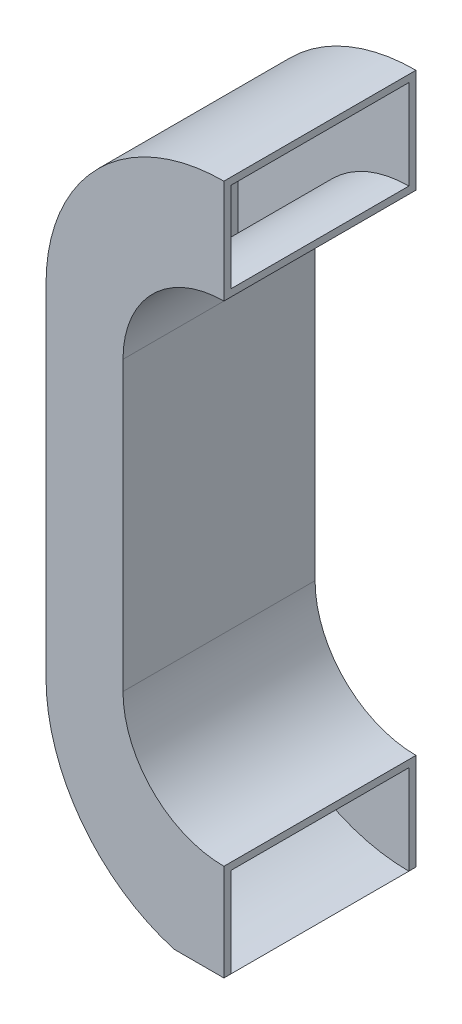
SolidWorks part; units mm, degrees
material "PE High Density"
ref_plane "Front Plane" through (0, 0, 0) normal (0, 0, 1) x (1, 0, 0)
ref_plane "Top Plane" through (0, 0, 0) normal (0, 1, 0) x (1, 0, 0)
ref_plane "Right Plane" through (0, 0, 0) normal (1, 0, 0) x (0, 0, -1)
sketch "Sketch2" plane through (0, 0, 0) normal (0, 0, 1) x (1, 0, 0)
  line L0 (0, 0) -> (0, 40)
  line L1 (0, 264.8) -> (0, 304.8)
  line L2 (-76.2, 76.2) -> (-76.2, 228.6)
  line L3 (0, 304.8) -> (-76.2, 304.8) construction
  line L4 (0, 304.8) -> (0, 0)
  line L5 (0, 0) -> (-76.2, 0) construction
  line L6 (-76.2, 304.8) -> (-76.2, 0) construction
  line L7 (-48.2, 88.2) -> (-48.2, 216.6)
  line L8 (-75.1148, 63.3856) -> (-26.4598, 4.7415) construction
  line L9 (-26.4598, 4.7415) -> (-6.9118, 20.9598) construction
  line L10 (-6.9118, 20.9598) -> (-55.5667, 79.6039) construction
  line L11 (-55.5667, 79.6039) -> (-75.1148, 63.3856) construction
  line L12 (0, 40) -> (25.7324, 40) construction
  line L13 (0, 264.8) -> (32.4991, 264.8) construction
  line L14 (0, 304.8) -> (0, 307.975)
  line L15 (0, 0) -> (-22.225, 0)
  line L16 (-45.025, 88.2) -> (-45.025, 216.6)
  line L17 (0, 261.625) -> (37.4536, 261.625) construction
  line L18 (0, 43.175) -> (15.6098, 43.175) construction
  line L19 (-79.375, 76.2) -> (-79.375, 228.6)
  line L20 (0, 307.975) -> (23.2649, 307.975) construction
  arc A0 (0, 304.8) -> (-76.2, 228.6) centre (0, 228.6) ccw
  arc A1 (0, 0) -> (-76.2, 76.2) centre (0, 76.2) cw
  arc A2 (0, 40) -> (-48.2, 88.2) centre (0, 88.2) cw
  arc A3 (0, 264.8) -> (-48.2, 216.6) centre (0, 216.6) ccw
  arc A4 (-45.025, 216.6) -> (0, 261.625) centre (0, 216.6) cw
  arc A5 (-45.025, 88.2) -> (0, 43.175) centre (0, 88.2) ccw
  arc A6 (-22.225, 0) -> (-79.375, 76.2) centre (0, 76.2) cw
  arc A7 (0, 307.975) -> (-79.375, 228.6) centre (0, 228.6) ccw
  dimension "D1" = 40
  dimension "D2" = 40
  dimension "D3" = 304.8
  dimension "D4" = 76.2
  dimension "D5" = 28
  dimension "D6" = 25.4
  dimension "D7" = 76.2
  dimension "D8" = 3.175
  dimension "D9" = 3.175
extrude "Boss-Extrude1" add sketch "Sketch2" along normal blind 79.375 contours L14 A7 L19 A6 L15 A1 L2 A0 | A5 L16 A4 L4 A3 L7 A2
sketch "Sketch3" plane through (0, 0, 79.375) normal (0, 0, 1) x (1, 0, 0)
  line L0 (-45.025, 88.2) -> (-45.025, 216.6) construction
  line L1 (0, 261.625) -> (0, 264.8) construction
  line L2 (-48.2, 216.6) -> (-48.2, 88.2) construction
  line L3 (0, 40) -> (0, 43.175) construction
  line L4 (0, 304.8) -> (0, 307.975) construction
  line L5 (-79.375, 228.6) -> (-79.375, 76.2) construction
  line L6 (-22.225, 0) -> (0, 0) construction
  line L7 (-76.2, 76.2) -> (-76.2, 228.6) construction
  line L8 (-45.025, 88.2) -> (-45.025, 216.6)
  line L9 (0, 261.625) -> (0, 264.8) construction
  line L10 (-48.2, 216.6) -> (-48.2, 88.2) construction
  line L11 (0, 40) -> (0, 43.175) construction
  line L12 (0, 304.8) -> (0, 307.975) construction
  line L13 (-79.375, 228.6) -> (-79.375, 76.2)
  line L14 (-22.225, 0) -> (0, 0) construction
  line L15 (-76.2, 76.2) -> (-76.2, 228.6) construction
  line L16 (0, 261.625) -> (0, 307.975)
  line L17 (0, 43.175) -> (0, 0)
  line L18 (0, 0) -> (-22.225, 0)
  arc A0 (-45.025, 88.2) -> (0, 43.175) centre (0, 88.2) ccw construction
  arc A1 (0, 261.625) -> (-45.025, 216.6) centre (0, 216.6) ccw construction
  arc A2 (0, 264.8) -> (-48.2, 216.6) centre (0, 216.6) ccw construction
  arc A3 (-48.2, 88.2) -> (0, 40) centre (0, 88.2) ccw construction
  arc A4 (0, 307.975) -> (-79.375, 228.6) centre (0, 228.6) ccw construction
  arc A5 (-79.375, 76.2) -> (-22.225, 0) centre (0, 76.2) ccw construction
  arc A6 (-76.2, 76.2) -> (0, 0) centre (0, 76.2) ccw construction
  arc A7 (0, 304.8) -> (-76.2, 228.6) centre (0, 228.6) ccw construction
  arc A8 (-45.025, 88.2) -> (0, 43.175) centre (0, 88.2) ccw
  arc A9 (0, 261.625) -> (-45.025, 216.6) centre (0, 216.6) ccw
  arc A10 (0, 264.8) -> (-48.2, 216.6) centre (0, 216.6) ccw construction
  arc A11 (-48.2, 88.2) -> (0, 40) centre (0, 88.2) ccw construction
  arc A12 (0, 307.975) -> (-79.375, 228.6) centre (0, 228.6) ccw
  arc A13 (-79.375, 76.2) -> (-22.225, 0) centre (0, 76.2) ccw
  arc A14 (-76.2, 76.2) -> (0, 0) centre (0, 76.2) ccw construction
  arc A15 (0, 304.8) -> (-76.2, 228.6) centre (0, 228.6) ccw construction
extrude "Boss-Extrude2" add sketch "Sketch3" along normal blind 3.175
sketch "Sketch4" plane through (0, 0, 0) normal (0, 0, -1) x (-1, 0, 0)
  line L0 (0, 307.975) -> (0, 304.8) construction
  line L1 (76.2, 228.6) -> (76.2, 76.2) construction
  line L2 (0, 0) -> (22.225, 0) construction
  line L3 (79.375, 76.2) -> (79.375, 228.6) construction
  line L4 (0, 43.175) -> (0, 40) construction
  line L5 (48.2, 88.2) -> (48.2, 216.6) construction
  line L6 (0, 264.8) -> (0, 261.625) construction
  line L7 (45.025, 216.6) -> (45.025, 88.2) construction
  line L8 (0, 307.975) -> (0, 304.8) construction
  line L9 (76.2, 228.6) -> (76.2, 76.2) construction
  line L10 (0, 0) -> (22.225, 0) construction
  line L11 (79.375, 76.2) -> (79.375, 228.6)
  line L12 (0, 43.175) -> (0, 40) construction
  line L13 (48.2, 88.2) -> (48.2, 216.6) construction
  line L14 (0, 264.8) -> (0, 261.625) construction
  line L15 (45.025, 216.6) -> (45.025, 88.2)
  line L16 (0, 307.975) -> (0, 261.625)
  line L17 (0, 43.175) -> (0, 0)
  line L18 (0, 0) -> (22.225, 0)
  arc A0 (76.2, 228.6) -> (0, 304.8) centre (0, 228.6) ccw construction
  arc A1 (0, 0) -> (76.2, 76.2) centre (0, 76.2) ccw construction
  arc A2 (22.225, 0) -> (79.375, 76.2) centre (0, 76.2) ccw construction
  arc A3 (79.375, 228.6) -> (0, 307.975) centre (0, 228.6) ccw construction
  arc A4 (0, 43.175) -> (45.025, 88.2) centre (0, 88.2) ccw construction
  arc A5 (0, 40) -> (48.2, 88.2) centre (0, 88.2) ccw construction
  arc A6 (48.2, 216.6) -> (0, 264.8) centre (0, 216.6) ccw construction
  arc A7 (45.025, 216.6) -> (0, 261.625) centre (0, 216.6) ccw construction
  arc A8 (76.2, 228.6) -> (0, 304.8) centre (0, 228.6) ccw construction
  arc A9 (0, 0) -> (76.2, 76.2) centre (0, 76.2) ccw construction
  arc A10 (22.225, 0) -> (79.375, 76.2) centre (0, 76.2) ccw
  arc A11 (79.375, 228.6) -> (0, 307.975) centre (0, 228.6) ccw
  arc A12 (0, 43.175) -> (45.025, 88.2) centre (0, 88.2) ccw
  arc A13 (0, 40) -> (48.2, 88.2) centre (0, 88.2) ccw construction
  arc A14 (48.2, 216.6) -> (0, 264.8) centre (0, 216.6) ccw construction
  arc A15 (45.025, 216.6) -> (0, 261.625) centre (0, 216.6) ccw
extrude "Boss-Extrude3" add sketch "Sketch4" along normal blind 3.175
